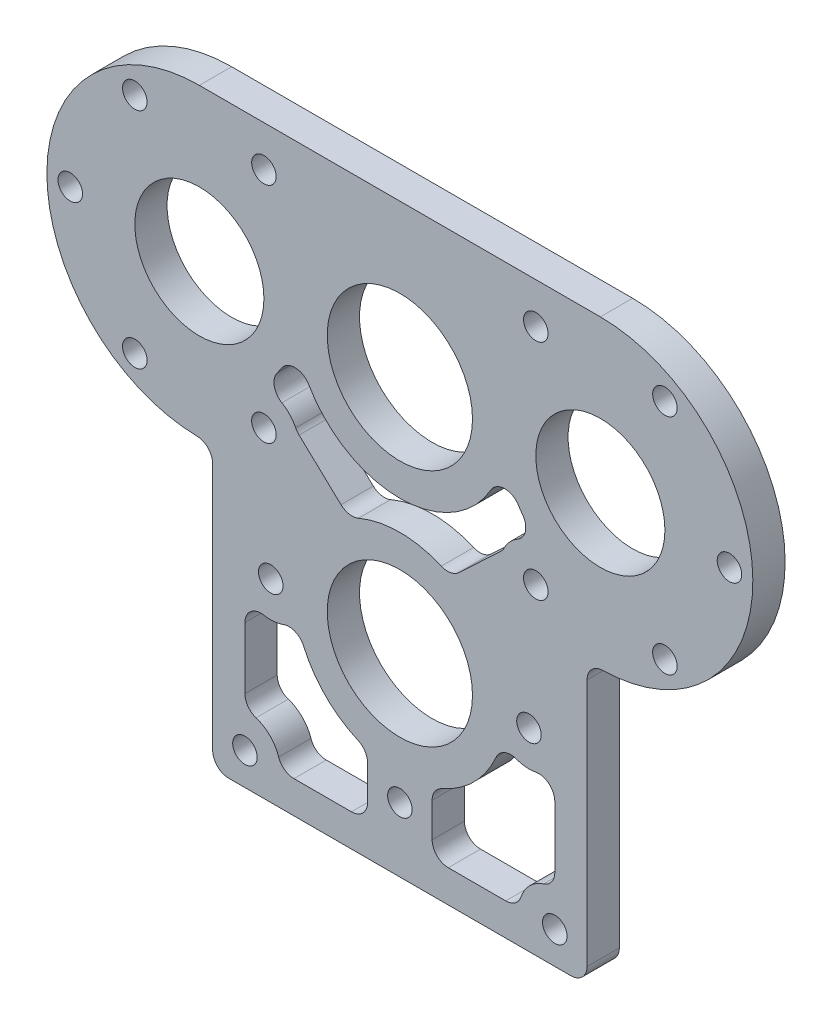
SolidWorks part; units mm, degrees
ref_plane "Front Plane" through (0, 0, 0) normal (0, 0, 1) x (1, 0, 0)
ref_plane "Top Plane" through (0, 0, 0) normal (0, 1, 0) x (1, 0, 0)
ref_plane "Right Plane" through (0, 0, 0) normal (1, 0, 0) x (0, 0, -1)
sketch "Sketch1" plane through (0, 0, 0) normal (0, 0, 1) x (1, 0, 0)
  line L0 (-39.4462, 47.0662) -> (0, 47.0662) construction
  line L1 (0, 47.0662) -> (39.4462, 47.0662) construction
  line L3 (36.83, -38.1) -> (36.83, 0)
  line L8 (39.4462, 77.0636) -> (-39.4462, 77.0636)
  line L13 (36.83, -38.1) -> (-36.83, -38.1)
  line L17 (0, -1000) -> (0, 49000) construction
  line L18 (-36.83, -38.1) -> (-36.83, 0)
  line L19 (36.83, 0) -> (36.83, 13.8985)
  line L20 (-36.83, 0) -> (-36.83, 13.8985)
  line L21 (39.4462, 47.0662) -> (39.4462, 72.4662) construction
  circle A0 centre (0, 47.0662) radius 14.2875
  circle A1 centre (-39.4462, 47.0662) radius 12.7
  circle A2 centre (39.4462, 47.0662) radius 12.7
  circle A3 centre (39.4462, 47.0662) radius 29.9974 construction
  circle A4 centre (-39.4462, 47.0662) radius 29.9974 construction
  circle A5 centre (0, 0) radius 14.2875
  arc A7 (39.9515, 17.0731) -> (39.4462, 77.0636) centre (39.4462, 47.0662) ccw
  circle A11 centre (0, 0) radius 38.1 construction
  circle A14 centre (0, 0) radius 36.83 construction
  circle A21 centre (39.4462, 47.0662) radius 25.4 construction
  circle A22 centre (52.1462, 69.0632) radius 2.413
  arc A25 (-39.9515, 17.0731) -> (-39.4462, 77.0636) centre (-39.4462, 47.0662) cw
  arc A28 (36.83, 13.8985) -> (39.9515, 17.0731) centre (40.005, 13.8985) cw
  arc A30 (-36.83, 13.8985) -> (-39.9515, 17.0731) centre (-40.005, 13.8985) ccw
  circle A32 centre (30.48, -31.75) radius 2.413
  circle A33 centre (-30.48, -31.75) radius 2.413
  circle A34 centre (0, -25.4) radius 2.413
  point P13 (0, -38.1)
  point P26 (0, 77.0636)
  point P45 (39.4462, 47.0662)
  dimension "D1" = 25.4
  dimension "D2" = 28.575
  dimension "D4" = 59.9948
  dimension "D7" = 47.0662
  dimension "D9" = 4.826
  dimension "D10" = 76.2
  dimension "D11" = 4.826
  dimension "D12" = 73.66
  dimension "D13" = 50.8
  dimension "D14" = 36.83
  dimension "D15" = 12.7
  dimension "D18" = 4.826
  dimension "D8" = 3.175
  dimension "D3" = 39.4462
  dimension "D5" = 0
  dimension "D6" = 38.1
  dimension "D17" = 6.35
  dimension "D19" = 6.35
  dimension "D16" = 30
extrude "Boss-Extrude1" add sketch "Sketch1" along normal blind 6.35
sketch "Sketch2" plane through (0, 0, 6.35) normal (0, 0, 1) x (1, 0, 0)
  line L1 (25.4, 0) -> (-25.4, 0) construction
  circle A4 centre (-25.4, 0) radius 2.413
  circle A6 centre (25.4, 0) radius 2.413
  dimension "D3" = 4.826
  dimension "D1" = 50.8
  dimension "D2" = 25.4
extrude "Cut-Extrude1" cut sketch "Sketch2" against normal through all
sketch "Sketch3" plane through (0, 0, 6.35) normal (0, 0, 1) x (1, 0, 0)
  line L1 (52.1462, 25.0692) -> (64.8462, 47.0662) construction
  line L2 (64.8462, 47.0662) -> (52.1462, 69.0632) construction
  line L3 (52.1462, 69.0632) -> (26.7462, 69.0632) construction
  line L4 (26.7462, 69.0632) -> (14.0462, 47.0662) construction
  line L5 (14.0462, 47.0662) -> (26.7462, 25.0692) construction
  line L6 (26.7462, 25.0692) -> (52.1462, 25.0692) construction
  line L7 (-52.1462, 69.0632) -> (-64.8462, 47.0662) construction
  line L8 (-64.8462, 47.0662) -> (-52.1462, 25.0692) construction
  line L9 (-52.1462, 25.0692) -> (-26.7462, 25.0692) construction
  line L10 (-26.7462, 25.0692) -> (-14.0462, 47.0662) construction
  line L11 (-14.0462, 47.0662) -> (-26.7462, 69.0632) construction
  line L12 (-26.7462, 69.0632) -> (-52.1462, 69.0632) construction
  circle A0 centre (39.4462, 47.0662) radius 25.4 construction
  circle A1 centre (-39.4462, 47.0662) radius 25.4 construction
  circle A2 centre (39.4462, 47.0662) radius 21.997 construction
  circle A3 centre (-39.4462, 47.0662) radius 21.997 construction
  circle A4 centre (-26.7462, 25.0692) radius 2.413
  circle A5 centre (-52.1462, 25.0692) radius 2.413
  circle A6 centre (-64.8462, 47.0662) radius 2.413
  circle A7 centre (-52.1462, 69.0632) radius 2.413
  circle A8 centre (-26.7462, 69.0632) radius 2.413
  circle A9 centre (26.7462, 25.0692) radius 2.413
  circle A10 centre (52.1462, 25.0692) radius 2.413
  circle A12 centre (52.1462, 69.0632) radius 2.413
  circle A13 centre (64.8462, 47.0662) radius 2.413
  circle A14 centre (26.7462, 69.0632) radius 2.413
  circle A20 centre (52.1462, 69.0632) radius 2.413 construction
  dimension "D1" = 50.8
  dimension "D2" = 4.826
extrude "Cut-Extrude2" cut sketch "Sketch3" against normal through all
fillet "Fillet1" radius 3.175 2 edges at (36.83, -38.1, 3.175) (-36.83, -38.1, 3.175)
sketch "Sketch4" plane through (0, 0, 6.35) normal (0, 0, 1) x (1, 0, 0)
  line L4 (0, 0) -> (-26.7462, 25.0692) construction
  line L5 (0, 0) -> (26.7462, 25.0692) construction
  line L6 (0, 0) -> (0, -31.75) construction
  line L7 (4.3425, 4.633) -> (-22.4037, 29.7022)
  line L8 (-30.48, -31.75) -> (30.48, -31.75)
  line L9 (30.48, -31.75) -> (30.48, 13.8985)
  line L10 (39.4462, 70.7136) -> (-39.4462, 70.7136)
  line L11 (-30.48, 13.8985) -> (-30.48, -31.75)
  line L12 (-30.48, -31.75) -> (30.48, -31.75)
  line L13 (30.48, -31.75) -> (30.48, 13.8985)
  line L14 (39.4462, 70.7136) -> (-39.4462, 70.7136)
  line L15 (-30.48, 13.8985) -> (-30.48, -31.75)
  line L16 (4.3425, -4.633) -> (31.0887, 20.4361)
  line L17 (-6.35, 0) -> (-6.35, -31.75)
  line L18 (-4.3425, -4.633) -> (-31.0887, 20.4361)
  line L19 (-4.3425, 4.633) -> (22.4037, 29.7022)
  line L20 (6.35, 0) -> (6.35, -31.75)
  circle A0 centre (0, 47.0662) radius 20.6375
  circle A1 centre (39.4462, 47.0662) radius 19.05
  circle A2 centre (26.7462, 25.0692) radius 6.985
  circle A3 centre (0, 0) radius 20.6375
  circle A4 centre (-26.7462, 25.0692) radius 6.985
  circle A5 centre (-39.4462, 47.0662) radius 19.05
  circle A6 centre (-30.48, -31.75) radius 6.985
  circle A7 centre (30.48, -31.75) radius 6.985
  circle A8 centre (25.4, 0) radius 6.985
  circle A9 centre (-25.4, 0) radius 6.985
  arc A26 (39.8445, 23.4222) -> (30.48, 13.8985) centre (40.005, 13.8985) ccw
  arc A28 (39.8445, 23.4222) -> (39.4462, 70.7136) centre (39.4462, 47.0662) ccw
  arc A29 (-39.4462, 70.7136) -> (-39.8445, 23.4222) centre (-39.4462, 47.0662) ccw
  arc A31 (-30.48, 13.8985) -> (-39.8445, 23.4222) centre (-40.005, 13.8985) ccw
  arc A32 (39.8445, 23.4222) -> (30.48, 13.8985) centre (40.005, 13.8985) ccw
  arc A34 (39.8445, 23.4222) -> (39.4462, 70.7136) centre (39.4462, 47.0662) ccw
  arc A35 (-39.4462, 70.7136) -> (-39.8445, 23.4222) centre (-39.4462, 47.0662) ccw
  arc A37 (-30.48, 13.8985) -> (-39.8445, 23.4222) centre (-40.005, 13.8985) ccw
  dimension "D1" = 38.1
  dimension "D2" = 41.275
  dimension "D3" = 13.97
  dimension "D4" = 6.35
  dimension "D5" = 6.35
  dimension "D6" = 6.35
extrude "Cut-Extrude4" cut sketch "Sketch4" against normal through all contours A5 A4 L7 A3 L19 A2 A1 A0 | A8 A3 L20 L12 A7 L13 | A9 L15 A6 L12 L17 A3
fillet "Fillet2" radius 3.175 20 edges at (-20.1235, -4.577, 3.175) (-6.35, -19.6363, 3.175) (-6.35, -31.75, 3.175) (-23.495, -31.75, 3.175) (-30.48, -24.765, 3.175) (30.48, -4.7941, 3.175) (30.48, -24.765, 3.175) (23.495, -31.75, 3.175) (6.35, -31.75, 3.175) (6.35, -19.6363, 3.175) (20.1235, -4.577, 3.175) (-30.48, -4.7941, 3.175) (20.5217, 44.8831, 3.175) (27.8269, 31.9701, 3.175) (20.2806, 27.7122, 3.175) (9.9843, 18.0616, 3.175) (-9.9843, 18.0616, 3.175) (-20.2806, 27.7122, 3.175) (-27.8269, 31.9701, 3.175) (-20.5217, 44.8831, 3.175)
